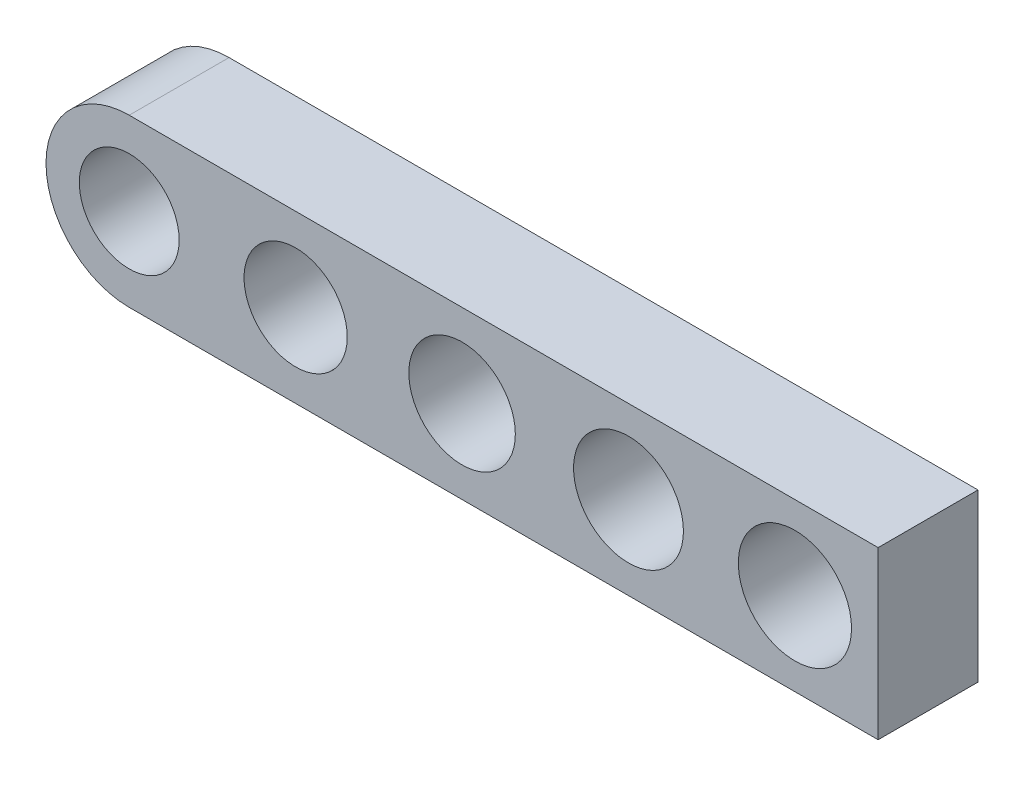
SolidWorks part; units mm, degrees
ref_plane "前视基准面" through (0, 0, 0) normal (0, 0, 1) x (1, 0, 0)
ref_plane "上视基准面" through (0, 0, 0) normal (0, 1, 0) x (1, 0, 0)
ref_plane "右视基准面" through (0, 0, 0) normal (1, 0, 0) x (0, 0, -1)
sketch "草图1" plane through (0, 0, 0) normal (0, 0, 1) x (1, 0, 0)
  line L0 (0, 0) -> (5, 0) construction
  line L1 (5, 0) -> (10, 0) construction
  line L2 (10, 0) -> (15, 0) construction
  line L3 (15, 0) -> (20, 0) construction
  line L4 (0, 2.5) -> (17.5, 2.5)
  line L5 (17.5, -2.5) -> (22.5, -2.5)
  line L7 (17.5, 2.5) -> (22.5, 2.5)
  line L8 (22.5, -2.5) -> (22.5, 2.5)
  line L9 (17.5, -2.5) -> (22.5, 2.5) construction
  line L10 (17.5, 2.5) -> (22.5, -2.5) construction
  line L11 (0, -2.5) -> (17.5, -2.5)
  circle A0 centre (0, 0) radius 1.5
  circle A1 centre (5, 0) radius 1.55
  circle A2 centre (10, 0) radius 1.6
  circle A3 centre (15, 0) radius 1.65
  circle A4 centre (20, 0) radius 1.7
  arc A5 (0, 2.5) -> (0, -2.5) centre (0, 0) ccw
extrude "凸台-拉伸1" add sketch "草图1" along normal blind 3
